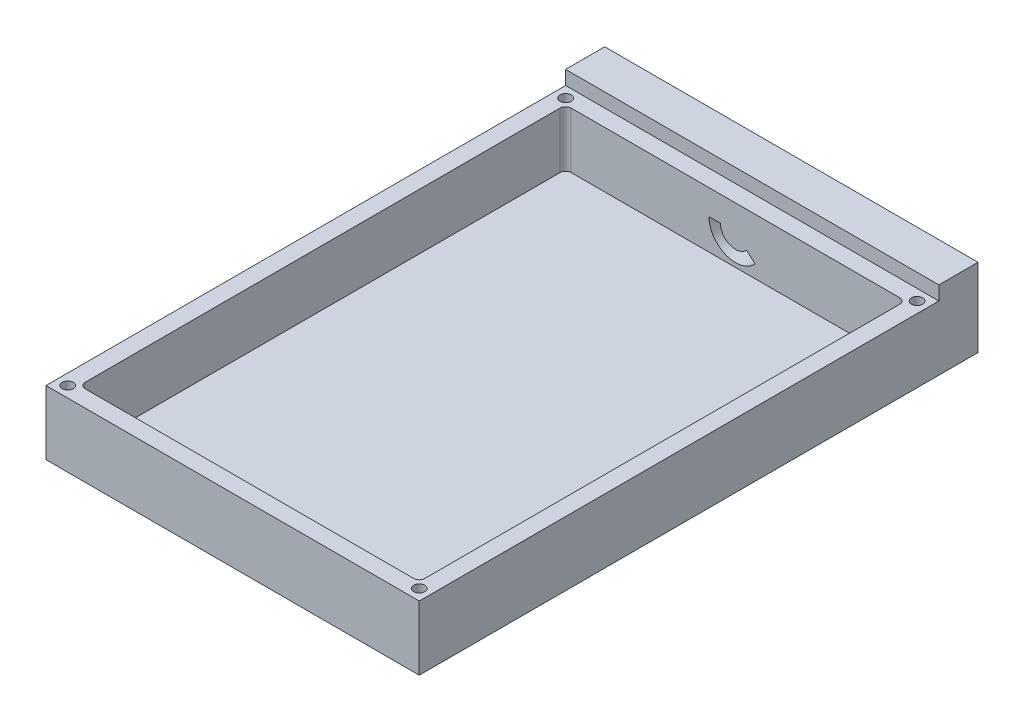
SolidWorks part; units mm, degrees
ref_plane "Front Plane" through (0, 0, 0) normal (0, 0, 1) x (1, 0, 0)
ref_plane "Top Plane" through (0, 0, 0) normal (0, 1, 0) x (1, 0, 0)
ref_plane "Right Plane" through (0, 0, 0) normal (1, 0, 0) x (0, 0, -1)
sketch "Sketch1" plane through (0, 0, 0) normal (0, 0, 1) x (1, 0, 0)
  line L1 (-33.4, 7) -> (33.4, 7)
  line L2 (-33.4, 7) -> (-33.4, -7)
  line L3 (-33.4, -7) -> (33.4, -7)
  line L4 (33.4, 7) -> (33.4, -7)
  line L5 (-33.4, 7) -> (33.4, -7) construction
  line L6 (-33.4, -7) -> (33.4, 7) construction
  circle A0 centre (0, 0) radius 1.1
  point P3 (0, 0)
  dimension "D1" = 2.2
  dimension "D2" = 7
  dimension "D3" = 14
  dimension "D4" = 66.8
extrude "Boss-Extrude2" add sketch "Sketch1" along normal blind 7
sketch "Sketch5" plane through (0, 0, 7) normal (0, 0, 1) x (1, 0, 0)
  line L0 (33.4, -7) -> (33.4, 7) construction
  line L1 (-33.4, -7) -> (33.4, -7)
  line L2 (-33.4, -7) -> (-33.4, -5.5)
  line L3 (-33.4, -5.5) -> (33.4, -5.5)
  line L4 (33.4, -7) -> (33.4, -5.5)
  dimension "D1" = 1.5
extrude "Boss-Extrude3" add sketch "Sketch5" along normal blind 93
sketch "Sketch6" plane through (0, -5.5, 0) normal (0, 1, 0) x (1, 0, 0)
  line L0 (-30.4, -97) -> (-30.4, -10)
  line L2 (33.4, -100) -> (33.4, -7) construction
  line L3 (33.4, -7) -> (-33.4, -7) construction
  line L4 (-33.4, -100) -> (-33.4, -7) construction
  line L5 (33.4, -100) -> (-33.4, -100)
  line L6 (33.4, -100) -> (33.4, -7)
  line L7 (33.4, -7) -> (-33.4, -7)
  line L8 (-33.4, -100) -> (-33.4, -7)
  line L9 (30.4, -10) -> (-30.4, -10)
  line L10 (30.4, -97) -> (30.4, -10)
  line L11 (30.4, -97) -> (-30.4, -97)
  circle A0 centre (-31.45, -8.95) radius 1
  circle A1 centre (31.45, -8.95) radius 1
  circle A2 centre (31.45, -98.05) radius 1
  circle A3 centre (-31.45, -98.05) radius 1
  dimension "D1" = 2
  dimension "D2" = 2
  dimension "D3" = 2
  dimension "D4" = 2
  dimension "D5" = 1.95
  dimension "D6" = 1.95
  dimension "D7" = 1.95
  dimension "D8" = 1.95
  dimension "D9" = 3
extrude "Boss-Extrude4" add sketch "Sketch6" along normal blind 10
fillet "Fillet1" radius 1 4 edges at (30.4, -0.5, 97) (-30.4, -0.5, 97) (30.4, -0.5, 10) (-30.4, -0.5, 10)
sketch "Sketch2" plane through (0, 0, 0) normal (0, 0, -1) x (-1, 0, 0)
  line L10 (2.7, 0) -> (4.75, 0)
  line L11 (-1.9895, -1.8254) -> (-3.5, -3.2113)
  line L12 (0, -2.7) -> (0, -4.75) construction
  arc A12 (-3.5, -3.2113) -> (4.75, 0) centre (0, 0) ccw
  arc A13 (-1.9895, -1.8254) -> (2.7, 0) centre (0, 0) ccw
  dimension "D1" = 9.5
  dimension "D2" = 3.5
  dimension "D3" = 5.4
extrude "Cut-Extrude1" cut sketch "Sketch2" against normal up to surface (10 mm away) up to face at (0, -0.5, 10)
sketch "Sketch7" plane through (0, -5.5, 0) normal (0, 1, 0) x (1, 0, 0)
  line L0 (-29.4, -97) -> (29.4, -97) construction
  line L1 (-28, -30) -> (28, -30)
  line L2 (-28, -30) -> (-28, -95)
  line L3 (-28, -95) -> (28, -95)
  line L4 (28, -30) -> (28, -95)
  line L5 (-28, -30) -> (28, -95) construction
  line L6 (-28, -95) -> (28, -30) construction
  point P0 (0, -62.5)
  point P7 (0, -97)
  dimension "D1" = 56
  dimension "D2" = 65
  dimension "D3" = 2
sketch "Sketch8" plane through (0, 4.5, 0) normal (0, 1, 0) x (1, 0, 0)
  line L0 (29.4, -10) -> (-29.4, -10) construction
  line L1 (-30.3, -10.75) -> (30.3, -10.75)
  line L2 (-30.3, -10.75) -> (-30.3, -96.25)
  line L3 (-30.3, -96.25) -> (30.3, -96.25)
  line L4 (30.3, -10.75) -> (30.3, -96.25)
  line L5 (-30.3, -10.75) -> (30.3, -96.25) construction
  line L6 (-30.3, -96.25) -> (30.3, -10.75) construction
  line L7 (-30.4, -53.5) -> (30.4, -53.5) construction
  line L8 (-30.4, -11) -> (-30.4, -96) construction
  line L9 (30.4, -96) -> (30.4, -11) construction
  point P0 (0, -53.5)
  point P7 (0, -10)
  point P14 (30.3, -53.5)
  dimension "D1" = 85.5
  dimension "D2" = 60.6
